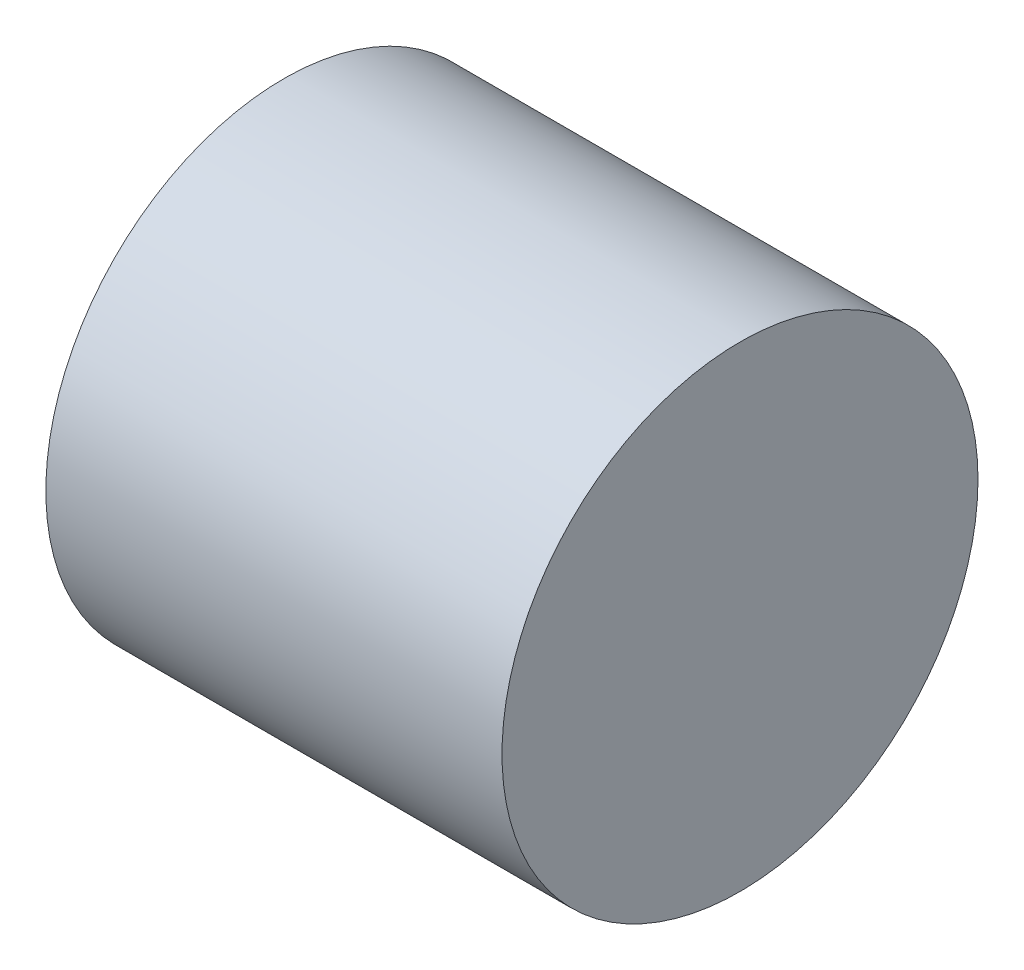
SolidWorks part; units mm, degrees
ref_plane "Front Plane" through (0, 0, 0) normal (0, 0, 1) x (1, 0, 0)
ref_plane "Top Plane" through (0, 0, 0) normal (0, 1, 0) x (1, 0, 0)
ref_plane "Right Plane" through (0, 0, 0) normal (1, 0, 0) x (0, 0, -1)
sketch "Sketch1" plane through (0, 0, 0) normal (1, 0, 0) x (0, 0, -1)
  circle A0 centre (0, 0) radius 12
  dimension "D1" = 24
extrude "Boss-Extrude1" add sketch "Sketch1" along normal blind 23
sketch "Sketch2" plane through (0, 0, 0) normal (-1, 0, 0) x (0, 0, 1)
  line L0 (-3.3541, -1) -> (3.3541, -1)
  circle A0 centre (0, 0) radius 3.5
  dimension "D1" = 7
  dimension "D2" = 1
extrude "Cut-Extrude1" cut sketch "Sketch2" against normal blind 10 contours L0 A0
